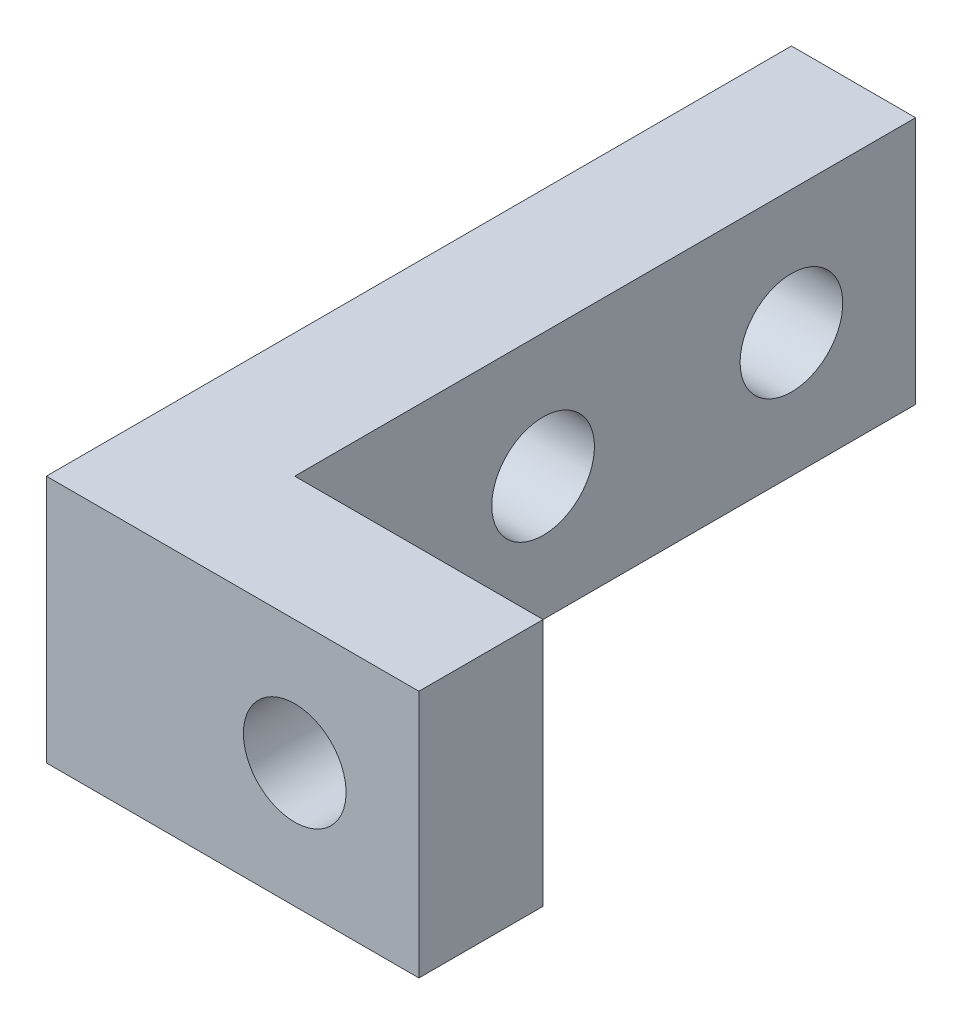
SolidWorks part; units mm, degrees
ref_plane "Front Plane" through (0, 0, 0) normal (0, 0, 1) x (1, 0, 0)
ref_plane "Top Plane" through (0, 0, 0) normal (0, 1, 0) x (1, 0, 0)
ref_plane "Right Plane" through (0, 0, 0) normal (1, 0, 0) x (0, 0, -1)
sketch "Sketch1" plane through (0, 0, 0) normal (0, 1, 0) x (1, 0, 0)
  line L1 (0, 0) -> (6.35, 0)
  line L2 (0, 0) -> (0, 38.1)
  line L3 (0, 38.1) -> (6.35, 38.1)
  line L4 (6.35, 0) -> (6.35, 38.1)
  line L5 (6.35, 6.35) -> (19.05, 6.35)
  line L6 (6.35, 6.35) -> (6.35, 0)
  line L7 (6.35, 0) -> (19.05, 0)
  line L8 (19.05, 6.35) -> (19.05, 0)
  dimension "D1" = 6.35
  dimension "D2" = 6.35
  dimension "D3" = 38.1
  dimension "D4" = 12.7
extrude "Boss-Extrude1" add sketch "Sketch1" along normal blind 12.7 contours L1 L4 L3 L2 | L8 L5 L4 L7
hole_wizard "Ø5.0mm Dowel Hole1" positions "Sketch2" profile "Sketch3" hole size "Ø5.0" standard "ANSI Metric"
sketch "Sketch2" plane through (0, 0, 0) normal (-1, 0, 0) x (0, 0, 1)
  line L0 (-38.1, 12.7) -> (-38.1, 0) construction
  point P0 (-31.75, 6.35)
  point P5 (-38.1, 6.35)
  point P6 (-19.05, 6.35)
  point P9 (0, 0)
  dimension "D1" = 6.35
  dimension "D2" = 12.7
sketch "Sketch3" plane through (0, 6.35, -31.75) normal (0, 1, 0) x (0, 0, 1)
  line L0 (0, 0) -> (0, 11.4833)
  line L1 (0, 11.4833) -> (2.625, 9.906)
  line L2 (2.625, 9.906) -> (2.625, 0)
  line L5 (2.625, 0) -> (0, 0)
  line L10 (0, 11.4833) -> (-2.625, 9.906) construction
  line L11 (0, -6.35) -> (0, 107.95) construction
  dimension "Hole Dia." = 5.25
  dimension "Hole Depth" = 9.906
  dimension "Drill Angle" = 118
hole_wizard "Ø5.0mm Dowel Hole2" positions "Sketch4" profile "Sketch5" hole size "Ø5.0" standard "ANSI Metric"
sketch "Sketch4" plane through (0, 0, -6.35) normal (0, 0, -1) x (-1, 0, 0)
  line L0 (-19.05, 12.7) -> (-19.05, 0) construction
  line L1 (-6.35, 0) -> (-19.05, 0) construction
  point P0 (-12.7, 6.35)
  point P5 (-19.05, 6.35)
  point P8 (-12.7, 0)
sketch "Sketch5" plane through (12.7, 6.35, -6.35) normal (1, 0, 0) x (0, 1, 0)
  line L0 (0, 0) -> (0, 11.4833)
  line L1 (0, 11.4833) -> (2.625, 9.906)
  line L2 (2.625, 9.906) -> (2.625, 0)
  line L5 (2.625, 0) -> (0, 0)
  line L10 (0, 11.4833) -> (-2.625, 9.906) construction
  line L11 (0, -6.35) -> (0, 107.95) construction
  dimension "Hole Dia." = 5.25
  dimension "Hole Depth" = 9.906
  dimension "Drill Angle" = 118
equation "\"acryllic thick\"= 0.25"
equation "\"height above table\"= 1.5in"
equation "\"D1@Sketch1\"=\"acryllic thick\""
equation "\"D2@Sketch1\"=\"acryllic thick\""
equation "\"D3@Sketch1\"=\"height above table\""
equation "\"press fit\" = 0.25mm"
